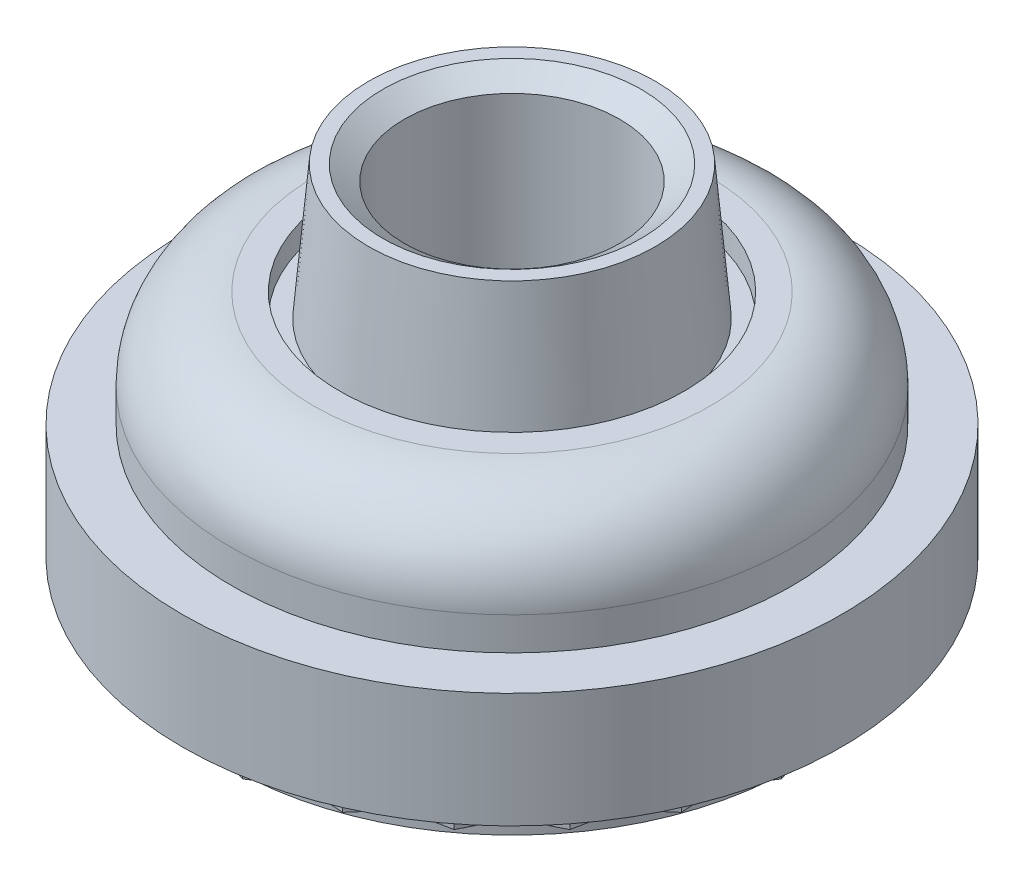
SolidWorks part; units mm, degrees
revolve "Body" add sketch "BodySke"
sketch "BodySke" plane through (0, 0, 0) normal (0, 0, 1) x (1, 0, 0)
  line L0 (6.316, 0) -> (7.65, 0)
  line L1 (7.65, 0) -> (7.65, 2.665)
  line L2 (3.3276, 7.9) -> (2.5, 7.9)
  line L3 (2.5, 7.9) -> (2.5, -0.97)
  line L4 (2.5, -0.97) -> (6.54, -0.97)
  line L5 (6.54, -0.97) -> (6.54, -0.776)
  line L6 (6.54, -0.776) -> (6.316, -0.388)
  line L7 (1.016, 1) -> (3.6522, 1) construction
  line L9 (0, 0) -> (0, 15.24) construction
  line L10 (6.316, -0.388) -> (6.316, 0)
  line L11 (3.6, 4.787) -> (4, 4.787)
  line L12 (4, 4.787) -> (4, 5.33)
  line L13 (4, 5.33) -> (4.6, 5.33)
  line L14 (7.65, 2.665) -> (6.5, 2.665)
  line L15 (6.5, 2.665) -> (6.5, 3.43)
  line L16 (3.6, 4.787) -> (3.3276, 7.9)
  arc A0 (6.5, 3.43) -> (4.6, 5.33) centre (4.6, 3.43) ccw
  dimension "E_dia" = 15.3
  dimension "C_dia" = 13.08
  dimension "A_ht" = 0.97
  dimension "Thread_min" = 5
  dimension "C_len" = 0.194
  dimension "Clinching_ht" = 0.388
  dimension "D1" = 60
  dimension "Advance" = 1
  dimension "T2_ht" = 7.9
  dimension "Guide_dia" = 8
  dimension "Top_flat_wid" = 0.6
  dimension "T1_ht" = 5.33
  dimension "T2_nl_lim" = 4.787
  dimension "D_dia" = 13
  dimension "Shoulder_ht" = 2.665
  dimension "Nose_dia" = 7.2
  dimension "Nose_ang" = 175
cosmetic thread "ThreadCosmetic" [suppressed]
revolve "EndChamfer" cut sketch "EndChamferSke" angle 360 about L0
sketch "EndChamferSke" plane through (0, 0, 0) normal (0, 0, 1) x (1, 0, 0)
  line L0 (0, -2.54) -> (0, 7.62) construction
  line L1 (0, 0) -> (0, 15.24) construction
  line L2 (3, -1.224) -> (3, -0.9675)
  line L3 (3, -0.9675) -> (2.5, -0.6175)
  line L4 (2.5, -0.6175) -> (2.5, -1.224)
  line L5 (2.5, -1.224) -> (3, -1.224)
  line L6 (3, 7.9) -> (2.5, 7.55)
  line L8 (2.5, 7.55) -> (2.5, 7.9)
  line L9 (3, 7.9) -> (2.5, 7.9)
  line L10 (2.5, 7.9) -> (-2.5, 7.9) construction
  line L11 (-6.54, -0.97) -> (6.54, -0.97) construction
  dimension "D1" = 0.254
  dimension "Thread_nominal" = 6
  dimension "D2" = 34.99
  dimension "Thread_min" = 5
  dimension "Inset" = 0.0025
ref_plane "Plane1" through (0, 0, 0) normal (0, 0, 1) x (1, 0, 0)
ref_plane "Plane2" through (0, 0, 0) normal (0, 1, 0) x (1, 0, 0)
ref_plane "Plane3" through (0, 0, 0) normal (1, 0, 0) x (0, 0, -1)
sketch "CliRinSegSke" plane through (0, 0, 0) normal (0, -1, 0) x (1, 0, 0)
  line L0 (0, 0) -> (0, 7.62) construction
  line L1 (0.9486, 7.2053) -> (0, 6.885)
  line L2 (0, 6.885) -> (-0.9486, 7.2053)
  line L3 (-0.9486, 7.2053) -> (-0.9201, 6.9892)
  line L4 (-0.9201, 6.9892) -> (0, 6.6785)
  line L5 (0, 6.6785) -> (0.9201, 6.9892)
  line L6 (0.9201, 6.9892) -> (0.9486, 7.2053)
  circle A0 centre (0, 0) radius 7.2675 construction
  circle A1 centre (0, 0) radius 6.885 construction
  circle A2 centre (0, 0) radius 6.6785 construction
  circle A3 centre (0, 0) radius 7.0495 construction
  circle A4 centre (0, 0) radius 6.54 construction
  dimension "Angle" = 15
  dimension "D2" = 14.099
  dimension "D3" = 13.77
  dimension "D4" = 13.3569
  dimension "D1" = 14.535
ref_plane "Plane4" through (0, -0.5486, 0) normal (0, 1, 0) x (-1, 0, 0)
sketch "ThdSchSke" plane through (0, 0, 0) normal (0, 0, 1) x (1, 0, 0)
  line L0 (0, -5.08) -> (0, 7.62) construction
  line L1 (0, 0) -> (0, 15.24) construction
  line L2 (0, -0.9675) -> (3, -0.9675) construction
  line L4 (3, -0.9675) -> (2.5, -0.6174)
  line L6 (3, -0.9675) -> (2.5, -1.3176)
  line L7 (2.5, -0.6174) -> (2.5, -1.3176)
  line L8 (3, -0.9675) -> (-3, -0.9675) construction
  dimension "Thread_min" = 5
  dimension "Thread_nominal" = 6
revolve "ThreadSchematic" [suppressed] cut sketch "ThdSchSke" angle 360 about L0
pattern_linear "ThdSchPat" [suppressed]
extrude "ClinchingRingSegment" add sketch "CliRinSegSke" along normal blind 0.388
pattern_circular "ClinchingRing" count 24 every 15 about axis through (0, 0, 0) along (0, 1, 0) of "ClinchingRingSegment"
sketch "SqrCutSke" plane through (0, -0.97, 0) normal (0, -1, 0) x (1, 0, 0)
  line L0 (3.6, -3.346) -> (3.6, 3.346)
  line L1 (3.346, 3.6) -> (-3.346, 3.6)
  line L2 (-3.6, 3.346) -> (-3.6, -3.346)
  line L3 (-3.346, -3.6) -> (3.346, -3.6)
  line L4 (-3.346, -3.981) -> (3.346, -3.981)
  line L5 (-3.981, 3.346) -> (-3.981, -3.346)
  line L6 (3.346, 3.981) -> (-3.346, 3.981)
  line L7 (3.981, -3.346) -> (3.981, 3.346)
  circle A0 centre (0, 0) radius 3.6 construction
  circle A1 centre (0, 0) radius 3.6 construction
  circle A4 centre (0, 0) radius 5.0912 construction
  arc A6 (-3.6, 3.346) -> (-3.346, 3.6) centre (-3.346, 3.346) cw
  arc A7 (3.6, 3.346) -> (3.346, 3.6) centre (3.346, 3.346) ccw
  arc A8 (3.346, -3.6) -> (3.6, -3.346) centre (3.346, -3.346) ccw
  arc A9 (-3.6, -3.346) -> (-3.346, -3.6) centre (-3.346, -3.346) ccw
  arc A10 (-3.981, -3.346) -> (-3.346, -3.981) centre (-3.346, -3.346) ccw
  arc A11 (-3.981, 3.346) -> (-3.346, 3.981) centre (-3.346, 3.346) cw
  arc A12 (3.981, 3.346) -> (3.346, 3.981) centre (3.346, 3.346) ccw
  arc A13 (3.346, -3.981) -> (3.981, -3.346) centre (3.346, -3.346) ccw
  point P12 (-3.6, 3.6)
  point P15 (3.6, 3.6)
  point P18 (3.6, -3.6)
  point P21 (-3.6, -3.6)
  dimension "D1" = 0.254
  dimension "D2" = 0.381
extrude "SqrCut" cut sketch "SqrCutSke" against normal blind 0.97
equation "' \"A_ht@BodySke\" = 0.97"
equation "' \"C_dia@BodySke\" = 13.08"
equation "' \"D_dia@BodySke\" = 13"
equation "' \"E_dia@BodySke\" = 15.3"
equation "' \"T1_ht@BodySke\" = 5.33"
equation "' \"T2_ht@BodySke\" = 7.9"
equation "' \"Advance@BodySke\" = 1"
equation "' \"Thread_min@BodySke\" = 5"
equation "' \"Thread_nominal@ThreadCosmetic\" = 6"
equation "' \"Nose_ang@BodySke\" = 175"
equation "' \"T2_ht@BodySke\" =  \"T1_ht@BodySke\" * 0.9 ' make NL"
equation "' \"T2_ht@BodySke\" = \"T1_ht@BodySke\" * 0.9 ' make NL"
equation "\"Nose_dia@BodySke\" = \"Thread_nominal@ThreadCosmetic\" * 1.2"
equation "\"Top_flat_wid@BodySke\" = \"Thread_nominal@ThreadCosmetic\" * 0.1"
equation "\"Guide_dia@BodySke\" = \"Nose_dia@BodySke\" + 0.8"
equation "\"T2_nl_lim@BodySke\" = \"T1_ht@BodySke\" * 0.9 - 0.01"
equation "\"Shoulder_ht@BodySke\" = \"T1_ht@BodySke\" * 0.5"
equation "\"Depth@SqrCut\" = \"A_ht@BodySke\""
equation "\"Count@ClinchingRing\" = 24"
equation "\"Angle@ClinchingRing\" = 360 / \"Count@ClinchingRing\""
equation "\"Angle@CliRinSegSke\" = 360 / \"Count@ClinchingRing\""
equation "\"D1@CliRinSegSke\" = \"E_dia@BodySke\" * 0.95"
equation "\"D2@CliRinSegSke\" = \"D1@CliRinSegSke\" * 0.97"
equation "\"D3@CliRinSegSke\" = \"E_dia@BodySke\" * 0.9"
equation "\"D4@CliRinSegSke\" = \"D3@CliRinSegSke\" * 0.97"
equation "\"C_len@BodySke\" = \"A_ht@BodySke\" * 0.2"
equation "\"Clinching_ht@BodySke\" = \"A_ht@BodySke\" * 0.4"
equation "\"Clinching_ht@ClinchingRingSegment\" =  \"A_ht@BodySke\" * 0.4"
equation "\"Thread_nominal@EndChamferSke\" = \"Thread_nominal@ThreadCosmetic\""
equation "\"Thread_min@EndChamferSke\" = \"Thread_min@BodySke\""
equation "\"D2@EndChamferSke\" = \"Vee_angle@ThdSchSke\" / 2 - 0.01"
equation "\"Thread_nominal@ThdSchSke\" = \"Thread_nominal@ThreadCosmetic\""
equation "\"Thread_min@ThdSchSke\" = \"Thread_min@BodySke\""
equation "\"Num_threads@ThdSchPat\" = int(  ( \"A_ht@BodySke\" + \"T2_ht@BodySke\" - \"Inset@EndChamferSke\" ) / \"Advance@BodySke\" + 0.999 )  + 1"
equation "\"Advance@ThdSchPat\" = (  \"A_ht@BodySke\" + \"T2_ht@BodySke\" - \"Inset@EndChamferSke\"  ) /  (\"Num_threads@ThdSchPat\" - 1) 'relax it"
